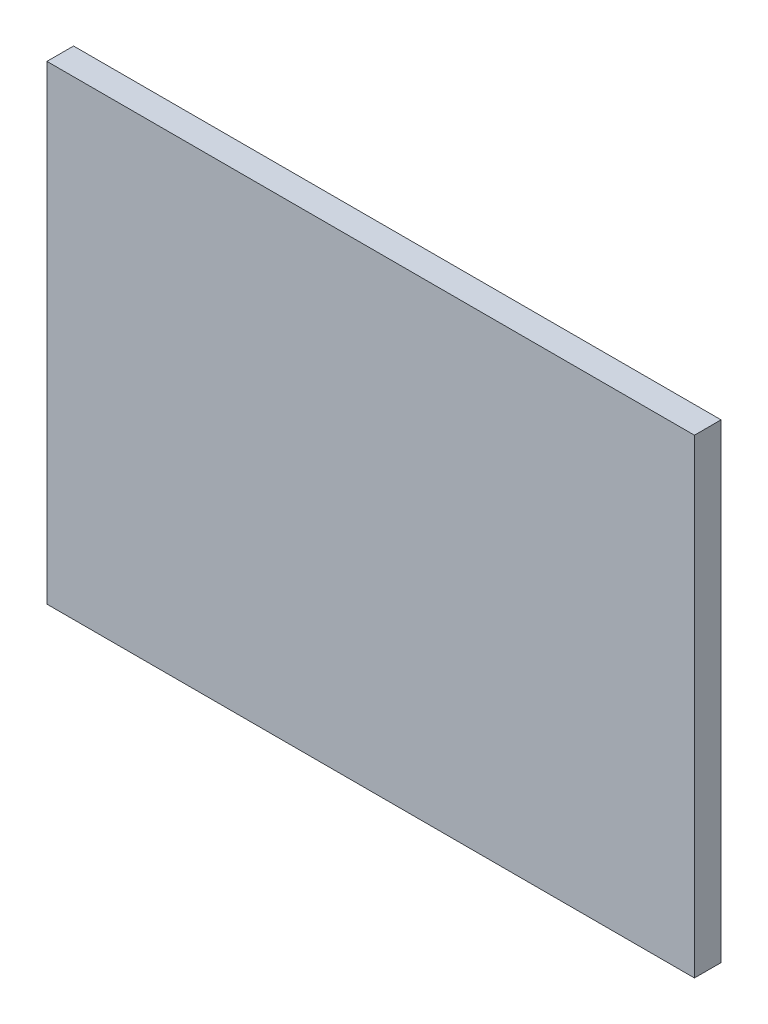
SolidWorks part; units mm, degrees
ref_plane "Front Plane" through (0, 0, 0) normal (0, 0, 1) x (1, 0, 0)
ref_plane "Top Plane" through (0, 0, 0) normal (0, 1, 0) x (1, 0, 0)
ref_plane "Right Plane" through (0, 0, 0) normal (1, 0, 0) x (0, 0, -1)
sketch "Sketch1" plane through (0, 0, 0) normal (0, 0, 1) x (1, 0, 0)
  line L1 (36.5, 26.5) -> (-36.5, 26.5)
  line L2 (36.5, 26.5) -> (36.5, -26.5)
  line L3 (36.5, -26.5) -> (-36.5, -26.5)
  line L4 (-36.5, 26.5) -> (-36.5, -26.5)
  line L5 (36.5, 26.5) -> (-36.5, -26.5) construction
  line L6 (36.5, -26.5) -> (-36.5, 26.5) construction
  point P0 (0, 0)
  dimension "D1" = 73
  dimension "D2" = 53
extrude "Boss-Extrude1" add sketch "Sketch1" along normal blind 3
